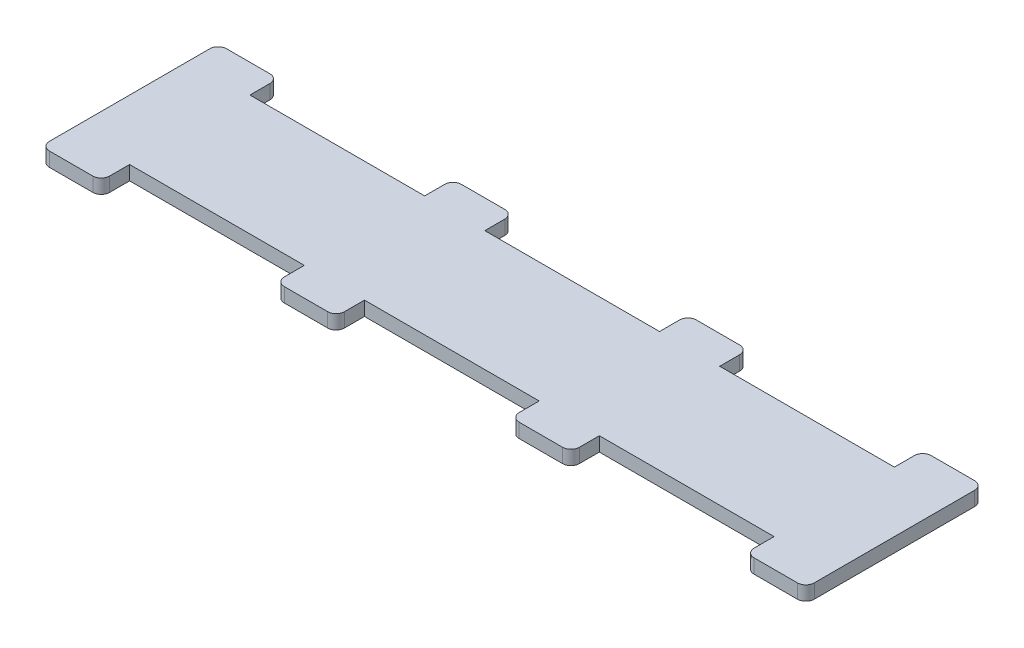
SolidWorks part; units mm, degrees
ref_plane "Front Plane" through (0, 0, 0) normal (0, 0, 1) x (1, 0, 0)
ref_plane "Top Plane" through (0, 0, 0) normal (0, 1, 0) x (1, 0, 0)
ref_plane "Right Plane" through (0, 0, 0) normal (1, 0, 0) x (0, 0, -1)
sketch "Sketch1" plane through (0, 0, 0) normal (0, 1, 0) x (1, 0, 0)
  line L1 (-80.7212, -12.7) -> (80.7212, -12.7)
  line L2 (-80.7212, -12.7) -> (-80.7212, 12.7)
  line L3 (-80.7212, 12.7) -> (80.7212, 12.7)
  line L4 (80.7212, -12.7) -> (80.7212, 12.7)
  line L5 (-80.7212, -12.7) -> (80.7212, 12.7) construction
  line L6 (-80.7212, 12.7) -> (80.7212, -12.7) construction
  point P0 (0, 0)
  dimension "D1" = 25.4
  dimension "D2" = 161.4424
extrude "Boss-Extrude1" add sketch "Sketch1" along normal blind 2.9972 contours L3 L4 L1 L2
sketch "Sketch2" plane through (0, 2.9972, 0) normal (0, 1, 0) x (1, 0, 0)
  line L0 (-80.7212, 12.7) -> (80.7212, 12.7) construction
  line L1 (-80.7212, 12.7) -> (-68.0212, 12.7)
  line L2 (-80.7212, 12.7) -> (-80.7212, 18.6944)
  line L3 (-80.7212, 18.6944) -> (-68.0212, 18.6944)
  line L4 (-68.0212, 12.7) -> (-68.0212, 18.6944)
  line L5 (-31.1404, 12.7) -> (-18.4404, 12.7)
  line L6 (-31.1404, 12.7) -> (-31.1404, 18.6944)
  line L7 (-31.1404, 18.6944) -> (-18.4404, 18.6944)
  line L8 (-18.4404, 12.7) -> (-18.4404, 18.6944)
  line L9 (-68.0212, 18.6944) -> (-31.1404, 18.6944) construction
  line L10 (18.4404, 12.7) -> (31.1404, 12.7)
  line L11 (18.4404, 12.7) -> (18.4404, 18.6944)
  line L12 (18.4404, 18.6944) -> (31.1404, 18.6944)
  line L13 (31.1404, 12.7) -> (31.1404, 18.6944)
  line L14 (80.7212, 12.7) -> (68.0212, 12.7)
  line L15 (80.7212, 12.7) -> (80.7212, 18.6944)
  line L16 (80.7212, 18.6944) -> (68.0212, 18.6944)
  line L17 (68.0212, 12.7) -> (68.0212, 18.6944)
  line L18 (-18.4404, 18.6944) -> (18.4404, 18.6944) construction
  line L19 (31.1404, 18.6944) -> (68.0212, 18.6944) construction
  dimension "D1" = 5.9944
  dimension "D2" = 12.7
extrude "Boss-Extrude2" add sketch "Sketch2" against normal up to surface (2.9972 mm away) up to face at (0, 0, 0)
fillet "Fillet1" radius 1.778 8 edges at (80.7212, 1.4986, -18.6944) (68.0212, 1.4986, -18.6944) (31.1404, 1.4986, -18.6944) (18.4404, 1.4986, -18.6944) (-18.4404, 1.4986, -18.6944) (-31.1404, 1.4986, -18.6944) (-68.0212, 1.4986, -18.6944) (-80.7212, 1.4986, -18.6944)
mirror "Mirror1" about plane through (0, 0, 0) normal (0, 0, 1) of "Boss-Extrude2", "Fillet1"
sketch "Sketch3" [suppressed] plane through (0, 0, 0) normal (0, -1, 0) x (1, 0, 0)
  line L0 (-77.5462, -9.525) -> (-77.5462, 9.525) construction
  line L1 (-77.5462, 9.525) -> (77.5462, 9.525) construction
  line L2 (77.5462, 9.525) -> (77.5462, -9.525) construction
  line L3 (77.5462, -9.525) -> (-77.5462, -9.525) construction
  line L4 (-77.5462, -9.525) -> (77.5462, 9.525) construction
  line L5 (77.5462, -9.525) -> (-77.5462, 9.525) construction
  line L6 (-68.0212, 12.7) -> (-31.1404, 12.7) construction
  line L7 (-80.7212, 16.9164) -> (-80.7212, -16.9164) construction
  line L20 (-77.5462, -9.525) -> (-46.5277, 9.525) construction
  line L21 (-46.5277, 9.525) -> (-15.5092, -9.525) construction
  line L22 (-15.5092, -9.525) -> (15.5092, 9.525) construction
  line L23 (15.5092, 9.525) -> (46.5277, -9.525) construction
  line L24 (46.5277, -9.525) -> (77.5462, 9.525) construction
  line L25 (77.5462, -9.525) -> (46.5277, 9.525) construction
  line L26 (46.5277, 9.525) -> (15.5092, -9.525) construction
  line L27 (15.5092, -9.525) -> (-15.5092, 9.525) construction
  line L28 (-15.5092, 9.525) -> (-46.5277, -9.525) construction
  line L29 (-46.5277, -9.525) -> (-77.5462, 9.525) construction
  line L30 (-46.5277, 9.525) -> (-46.5277, -9.525) construction
  line L31 (-15.5092, 9.525) -> (-15.5092, -9.525) construction
  line L32 (15.5092, 9.525) -> (15.5092, -9.525) construction
  line L33 (46.5277, -9.525) -> (46.5277, 9.525) construction
  line L34 (-77.5462, -9.525) -> (-46.5277, -9.525) construction
  line L35 (-46.5277, -9.525) -> (-15.5092, -9.525) construction
  line L36 (-15.5092, -9.525) -> (15.5092, -9.525) construction
  line L37 (15.5092, -9.525) -> (46.5277, -9.525) construction
  line L38 (46.5277, -9.525) -> (77.5462, -9.525) construction
  line L39 (-77.5462, 0) -> (-46.5277, 0) construction
  line L40 (-46.5277, 0) -> (-15.5092, 0) construction
  line L41 (-15.5092, 0) -> (15.5092, 0) construction
  line L42 (15.5092, 0) -> (46.5277, 0) construction
  line L43 (46.5277, 0) -> (77.5462, 0) construction
  line L44 (-45.8631, -8.4428) -> (-76.8816, 10.6072)
  line L45 (-76.8816, -10.6072) -> (-45.8631, 8.4428)
  line L46 (-77.5462, 8.255) -> (77.5462, 8.255)
  line L47 (77.5462, -8.255) -> (-77.5462, -8.255)
  line L48 (-76.2762, -9.525) -> (-76.2762, 9.525)
  line L49 (-47.7977, 9.525) -> (-47.7977, -9.525)
  line L50 (-16.1739, 10.6072) -> (-47.1924, -8.4428)
  line L51 (-47.1924, 8.4428) -> (-16.1739, -10.6072)
  line L52 (-16.7792, 9.525) -> (-16.7792, -9.525)
  line L53 (-14.8446, -10.6072) -> (16.1739, 8.4428)
  line L54 (16.1739, -8.4428) -> (-14.8446, 10.6072)
  line L55 (14.2392, 9.525) -> (14.2392, -9.525)
  line L56 (45.8631, 10.6072) -> (14.8446, -8.4428)
  line L57 (14.8446, 8.4428) -> (45.8631, -10.6072)
  line L58 (47.7977, -9.525) -> (47.7977, 9.525)
  line L59 (78.2108, -8.4428) -> (47.1924, 10.6072)
  line L60 (47.1924, -10.6072) -> (78.2108, 8.4428)
  line L61 (76.2762, 9.525) -> (76.2762, -9.525)
  line L62 (-47.1924, -10.6072) -> (-78.2108, 8.4428)
  line L63 (-78.2108, -8.4428) -> (-47.1924, 10.6072)
  line L64 (-77.5462, 10.795) -> (77.5462, 10.795)
  line L65 (77.5462, -10.795) -> (-77.5462, -10.795)
  line L66 (-78.8162, -9.525) -> (-78.8162, 9.525)
  line L67 (-45.2577, 9.525) -> (-45.2577, -9.525)
  line L68 (-14.8446, 8.4428) -> (-45.8631, -10.6072)
  line L69 (-45.8631, 10.6072) -> (-14.8446, -8.4428)
  line L70 (-14.2392, 9.525) -> (-14.2392, -9.525)
  line L71 (-16.1739, -8.4428) -> (14.8446, 10.6072)
  line L72 (14.8446, -10.6072) -> (-16.1739, 8.4428)
  line L73 (16.7792, 9.525) -> (16.7792, -9.525)
  line L74 (47.1924, 8.4428) -> (16.1739, -10.6072)
  line L75 (16.1739, 10.6072) -> (47.1924, -8.4428)
  line L76 (45.2577, -9.525) -> (45.2577, 9.525)
  line L77 (76.8816, -10.6072) -> (45.8631, 8.4428)
  line L78 (45.8631, -8.4428) -> (76.8816, 10.6072)
  line L79 (78.8162, 9.525) -> (78.8162, -9.525)
  arc A0 (-45.8631, -8.4428) -> (-47.1924, -10.6072) centre (-46.5277, -9.525) cw
  arc A1 (-76.8816, 10.6072) -> (-78.2108, 8.4428) centre (-77.5462, 9.525) ccw
  arc A2 (-76.8816, -10.6072) -> (-78.2108, -8.4428) centre (-77.5462, -9.525) cw
  arc A3 (-45.8631, 8.4428) -> (-47.1924, 10.6072) centre (-46.5277, 9.525) ccw
  arc A4 (-77.5462, 8.255) -> (-77.5462, 10.795) centre (-77.5462, 9.525) cw
  arc A5 (77.5462, 8.255) -> (77.5462, 10.795) centre (77.5462, 9.525) ccw
  arc A6 (77.5462, -8.255) -> (77.5462, -10.795) centre (77.5462, -9.525) cw
  arc A7 (-77.5462, -8.255) -> (-77.5462, -10.795) centre (-77.5462, -9.525) ccw
  arc A8 (-76.2762, -9.525) -> (-78.8162, -9.525) centre (-77.5462, -9.525) cw
  arc A9 (-76.2762, 9.525) -> (-78.8162, 9.525) centre (-77.5462, 9.525) ccw
  arc A10 (-47.7977, 9.525) -> (-45.2577, 9.525) centre (-46.5277, 9.525) cw
  arc A11 (-47.7977, -9.525) -> (-45.2577, -9.525) centre (-46.5277, -9.525) ccw
  arc A12 (-16.1739, 10.6072) -> (-14.8446, 8.4428) centre (-15.5092, 9.525) cw
  arc A13 (-47.1924, -8.4428) -> (-45.8631, -10.6072) centre (-46.5277, -9.525) ccw
  arc A14 (-47.1924, 8.4428) -> (-45.8631, 10.6072) centre (-46.5277, 9.525) cw
  arc A15 (-16.1739, -10.6072) -> (-14.8446, -8.4428) centre (-15.5092, -9.525) ccw
  arc A16 (-16.7792, 9.525) -> (-14.2392, 9.525) centre (-15.5092, 9.525) cw
  arc A17 (-16.7792, -9.525) -> (-14.2392, -9.525) centre (-15.5092, -9.525) ccw
  arc A18 (-14.8446, -10.6072) -> (-16.1739, -8.4428) centre (-15.5092, -9.525) cw
  arc A19 (16.1739, 8.4428) -> (14.8446, 10.6072) centre (15.5092, 9.525) ccw
  arc A20 (16.1739, -8.4428) -> (14.8446, -10.6072) centre (15.5092, -9.525) cw
  arc A21 (-14.8446, 10.6072) -> (-16.1739, 8.4428) centre (-15.5092, 9.525) ccw
  arc A22 (14.2392, 9.525) -> (16.7792, 9.525) centre (15.5092, 9.525) cw
  arc A23 (14.2392, -9.525) -> (16.7792, -9.525) centre (15.5092, -9.525) ccw
  arc A24 (45.8631, 10.6072) -> (47.1924, 8.4428) centre (46.5277, 9.525) cw
  arc A25 (14.8446, -8.4428) -> (16.1739, -10.6072) centre (15.5092, -9.525) ccw
  arc A26 (14.8446, 8.4428) -> (16.1739, 10.6072) centre (15.5092, 9.525) cw
  arc A27 (45.8631, -10.6072) -> (47.1924, -8.4428) centre (46.5277, -9.525) ccw
  arc A28 (47.7977, -9.525) -> (45.2577, -9.525) centre (46.5277, -9.525) cw
  arc A29 (47.7977, 9.525) -> (45.2577, 9.525) centre (46.5277, 9.525) ccw
  arc A30 (78.2108, -8.4428) -> (76.8816, -10.6072) centre (77.5462, -9.525) cw
  arc A31 (47.1924, 10.6072) -> (45.8631, 8.4428) centre (46.5277, 9.525) ccw
  arc A32 (47.1924, -10.6072) -> (45.8631, -8.4428) centre (46.5277, -9.525) cw
  arc A33 (78.2108, 8.4428) -> (76.8816, 10.6072) centre (77.5462, 9.525) ccw
  arc A34 (76.2762, 9.525) -> (78.8162, 9.525) centre (77.5462, 9.525) cw
  arc A35 (76.2762, -9.525) -> (78.8162, -9.525) centre (77.5462, -9.525) ccw
  point P2 (0, 0)
  dimension "D1" = 3.175
  dimension "D2" = 3.175
  dimension "D3" = 1.27
  dimension "D4" = 1.27
